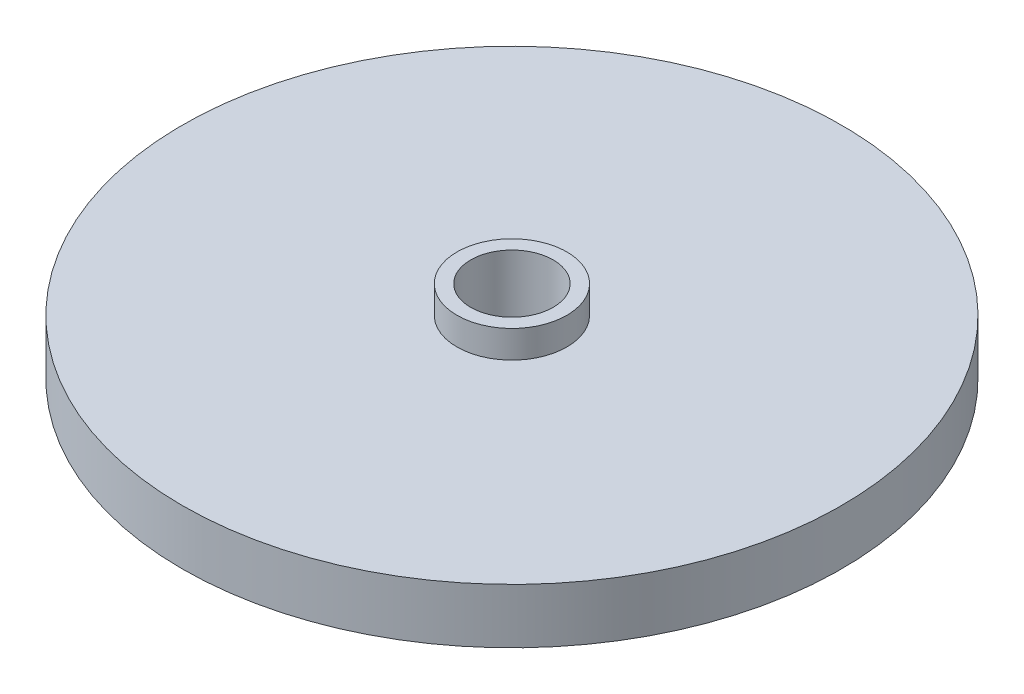
SolidWorks part; units mm, degrees
ref_plane "Спереди" through (0, 0, 0) normal (0, 0, 1) x (1, 0, 0)
ref_plane "Сверху" through (0, 0, 0) normal (0, 1, 0) x (1, 0, 0)
ref_plane "Справа" through (0, 0, 0) normal (1, 0, 0) x (0, 0, -1)
other "Configuration Table"
sketch "Sketch1" plane through (0, 0, 0) normal (0, 1, 0) x (1, 0, 0)
  circle A0 centre (0, 0) radius 12
  dimension "D1" = 24
extrude "Boss-Extrude1" add sketch "Sketch1" against normal blind 2
sketch "Sketch2" plane through (0, -2, 0) normal (0, -1, 0) x (1, 0, 0)
  circle A0 centre (0, 0) radius 4.5
  dimension "D1" = 9
extrude "Boss-Extrude2" add sketch "Sketch2" along normal blind 2
sketch "Sketch3" plane through (0, -4, 0) normal (0, -1, 0) x (1, 0, 0)
  circle A0 centre (0, 0) radius 1.5
  dimension "D1" = 3
extrude "Cut-Extrude1" cut sketch "Sketch3" against normal through all
sketch "Sketch4" plane through (0, 0, 0) normal (0, 1, 0) x (1, 0, 0)
  circle A0 centre (0, 0) radius 1.5
  circle A1 centre (0, 0) radius 2
  circle M3 centre (0, 0) radius 1.5
  dimension "D1" = 3
  dimension "D2" = 4
extrude "Boss-Extrude3" add sketch "Sketch4" along normal blind 1 contours A1 M3
